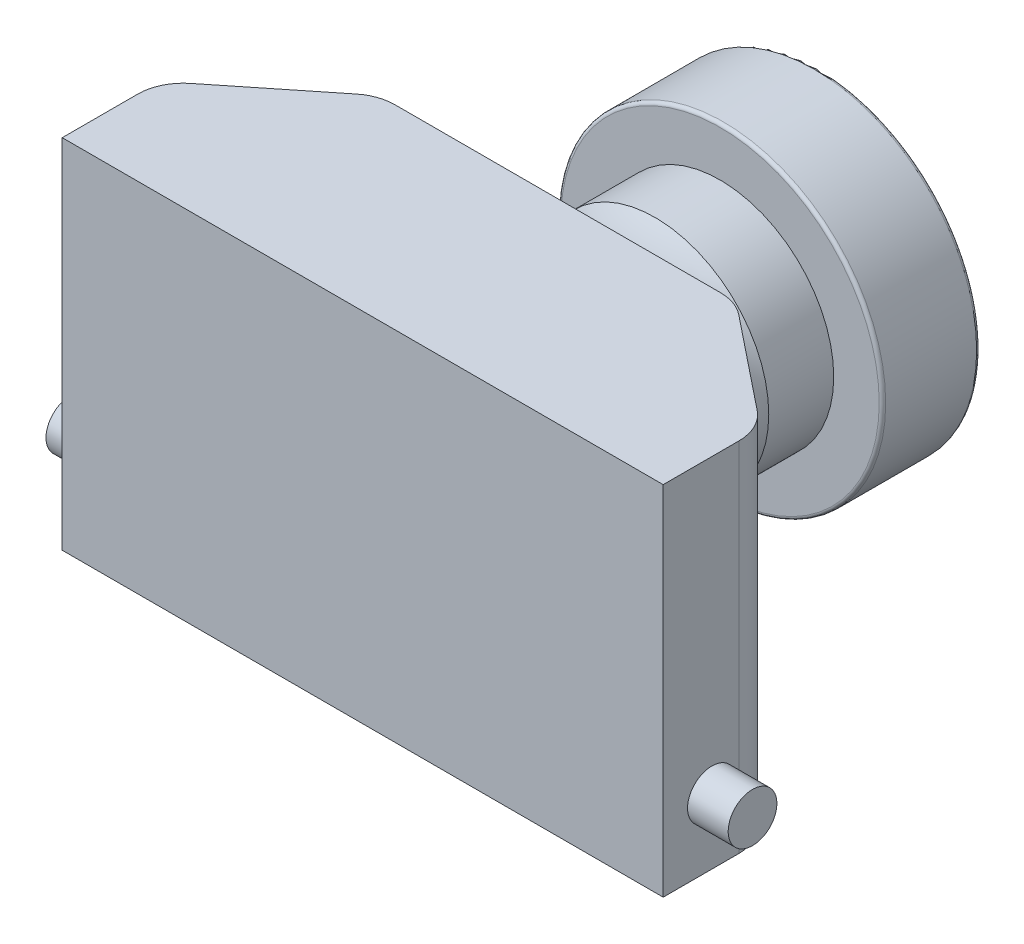
SolidWorks part; units mm, degrees
ref_plane "Ön Düzlem" through (0, 0, 0) normal (0, 0, 1) x (1, 0, 0)
ref_plane "Üst Düzlem" through (0, 0, 0) normal (0, 1, 0) x (1, 0, 0)
ref_plane "Sağ Düzlem" through (0, 0, 0) normal (1, 0, 0) x (0, 0, -1)
sketch "Çizim1" plane through (0, 0, 0) normal (0, 1, 0) x (1, 0, 0)
  line L0 (0, 0) -> (0, 13.1759) construction
  line L1 (-9.25, 0) -> (9.25, 0)
  line L2 (9.25, 3) -> (5.5, 6)
  line L3 (5.5, 6) -> (-5.5, 6)
  line L4 (-5.5, 6) -> (-9.25, 3)
  line L5 (-9.25, 3) -> (-9.25, 0)
  line L6 (9.25, 0) -> (9.25, 3)
  point P6 (0, 0)
  dimension "D1" = 18.5
  dimension "D2" = 3
  dimension "D3" = 3
  dimension "D4" = 3
  dimension "D5" = 11
extrude "Yükseklik-Ekstrüzyon1" add sketch "Çizim1" along normal mid plane 11
sketch "Çizim2" plane through (0, 0, 0) normal (0, 1, 0) x (1, 0, 0)
  line L0 (0, 0) -> (0, 17.6303) construction
  line L1 (-9.25, 0) -> (9.25, 0) construction
  line L2 (0, 6) -> (0, 13.8)
  line L3 (5.5, 6) -> (-5.5, 6) construction
  line L4 (0, 13.8) -> (4.5, 13.8)
  line L5 (4.5, 13.8) -> (4.5, 14)
  line L6 (4.5, 14) -> (5, 14)
  line L7 (5, 14) -> (5, 11)
  line L8 (5, 11) -> (3.5, 11)
  line L9 (3.5, 11) -> (3.5, 9)
  line L10 (0, 6) -> (4.5, 6)
  arc A0 (3.5, 9) -> (4.5, 6) centre (5.8371, 8.1124) ccw
  dimension "D8" = 4.5
  dimension "D9" = 2.5
  dimension "D1" = 7.8
  dimension "D2" = 5
  dimension "D3" = 0.5
  dimension "D4" = 0.2
  dimension "D5" = 3
  dimension "D6" = 1.5
  dimension "D7" = 2
revolve "Döndür1" add sketch "Çizim2" angle 360 about L0
sketch "Çizim3" plane through (0, 0, 0) normal (0, 1, 0) x (1, 0, 0)
  line L0 (0, 0) -> (0, 22.8485) construction
  line L1 (0, 13.8) -> (4.75, 13.8)
  line L2 (4.75, 13.8) -> (4.75, 14)
  line L4 (5, 14) -> (-5, 14) construction
  line L5 (0, 13.8) -> (0, 14.8)
  arc A0 (0, 14.8) -> (4.75, 14) centre (0.5329, 3.4625) cw
  dimension "D5" = 11.35
  dimension "D1" = 4.75
  dimension "D2" = 0.2
  dimension "D3" = 0.2
  dimension "D4" = 1
revolve "Döndür2" add sketch "Çizim3" angle 360 about L0
sketch "Çizim4" plane through (0, 0, 0) normal (1, 0, 0) x (0, 0, -1)
  line L0 (0, 5.5) -> (0, -5.5) construction
  line L1 (0, -5.5) -> (3, -5.5) construction
  circle A0 centre (1.5, -3.5) radius 0.75
  dimension "D3" = 1.5
  dimension "D1" = 1.5
  dimension "D2" = 2
extrude "Yükseklik-Ekstrüzyon2" add sketch "Çizim4" along normal mid plane 21
fillet "Radyus1" radius 0.1 3 edges at (-4.75, 0, -14) (5, 0, -11) (5, 0, -14)
fillet "Radyus2" radius 1.4 4 edges at (-9.25, 0, -3) (-5.5, 0, -6) (5.5, 0, -6) (9.25, 0, -3)
